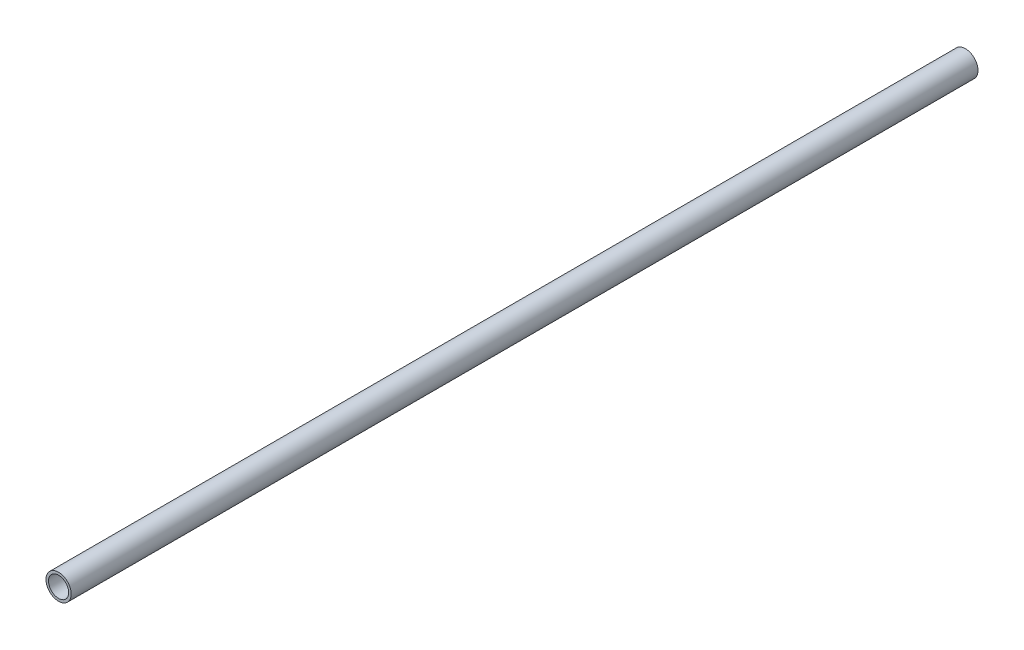
SolidWorks part; units mm, degrees
material "Delrin 2700 NC010, Low Viscosity Acetal Copolymer (SS)"
ref_plane "Front Plane" through (0, 0, 0) normal (0, 0, 1) x (1, 0, 0)
ref_plane "Top Plane" through (0, 0, 0) normal (0, 1, 0) x (1, 0, 0)
ref_plane "Right Plane" through (0, 0, 0) normal (1, 0, 0) x (0, 0, -1)
sketch "Sketch1" plane through (0, 0, 0) normal (0, 0, 1) x (1, 0, 0)
  circle A0 centre (0, 0) radius 3.175
  circle A2 centre (0, 0) radius 2.54
  dimension "D1" = 6.35
  dimension "D3" = 0.635
extrude "Boss-Extrude1" add sketch "Sketch1" along normal blind 228.6
